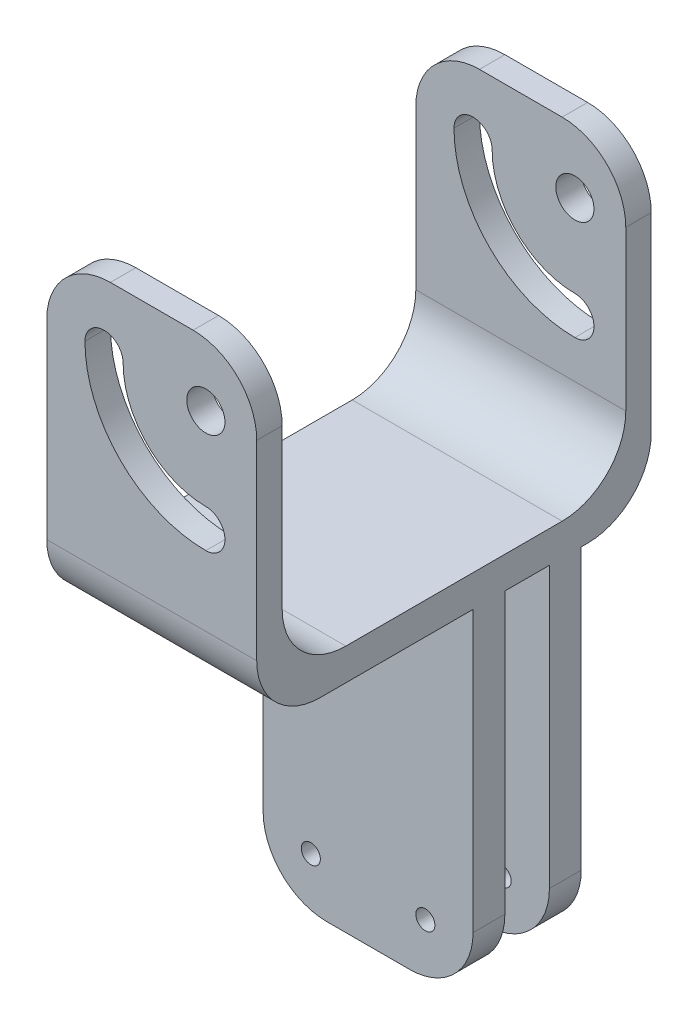
SolidWorks part; units mm, degrees
other "Marcação1"
sketch "Esboço5" plane through (0, 50, 68.25) normal (-0.797, 0.1637, 0.5813) x (0.5636, -0.1442, 0.8134)
material "Nylon - impressão"
ref_plane "Plano frontal" through (0, 0, 0) normal (0, 0, 1) x (1, 0, 0)
ref_plane "Plano superior" through (0, 0, 0) normal (0, 1, 0) x (1, 0, 0)
ref_plane "Plano direito" through (0, 0, 0) normal (1, 0, 0) x (0, 0, -1)
sketch "Esboço1" plane through (0, 0, 0) normal (0, 0, 1) x (1, 0, 0)
  line L0 (0, 0) -> (0, 50)
  line L1 (0, 50) -> (33, 50)
  line L2 (33, 50) -> (33, 0)
  line L3 (33, 0) -> (0, 0)
  line L4 (25, 40) -> (25, 37) construction
  circle A0 centre (25, 40) radius 3
  arc A2 (25, 24) -> (9, 40) centre (25, 40) cw construction
  arc A3 (6, 40) -> (25, 21) centre (25, 40) ccw
  arc A4 (12, 40) -> (25, 27) centre (25, 40) ccw
  arc A5 (12, 40) -> (6, 40) centre (9, 40) ccw
  arc A6 (25, 21) -> (25, 27) centre (25, 24) ccw
  point P10 (13.6863, 28.6863)
  dimension "D3" = 6
  dimension "D5" = 16
  dimension "D6" = 13
  dimension "D1" = 25
  dimension "D2" = 50
  dimension "D4" = 8
extrude "Ressalto-extrusão2" add sketch "Esboço1" along normal blind 62
sketch "Esboço3" plane through (0, 50, 0) normal (0, 1, 0) x (1, 0, 0)
  line L0 (0, -58) -> (33, -58)
  line L1 (0, -62) -> (0, 0) construction
  line L2 (33, -62) -> (33, 0) construction
  line L3 (33, -58) -> (33, -4)
  line L4 (33, -4) -> (0, -4)
  line L5 (0, -4) -> (0, -58)
  line L6 (33, 0) -> (0, 0) construction
  dimension "D1" = 4
  dimension "D2" = 4
extrude "Corte-extrusão1" cut sketch "Esboço3" against normal blind 45
sketch "Esboço7" plane through (0, 0, 0) normal (0, -1, 0) x (1, 0, 0)
  line L0 (0, 11) -> (33, 11)
  line L1 (33, 62) -> (33, 0) construction
  line L2 (0, 62) -> (0, 0) construction
  line L3 (33, 11) -> (33, 16)
  line L4 (33, 16) -> (0, 16)
  line L5 (0, 16) -> (0, 11)
  line L6 (0, 23) -> (33, 23)
  line L7 (33, 23) -> (33, 28)
  line L8 (33, 28) -> (0, 28)
  line L9 (0, 28) -> (0, 23)
  line L10 (33, 4) -> (0, 4) construction
  line L11 (33, 4) -> (0, 4)
  point P2 (0, 0)
  point P5 (0, 0)
  point P10 (0, 0)
  point P15 (0, 0)
  point P18 (0, 0)
  line M10 (33, 0) -> (33, 62)
  line M12 (0, 62) -> (0, 0)
  dimension "D1" = 5
  dimension "D2" = 5
  dimension "D3" = 7
  dimension "D4" = 7
extrude "Ressalto-extrusão3" add sketch "Esboço7" along normal blind 54 contours L8 L6 M10 M12 | L4 L0 M10 M12
sketch "Esboço10" plane through (0, 0, 11) normal (0, 0, -1) x (-1, 0, 0)
  line L0 (0, -54) -> (-33, -54) construction
  line L3 (-7.5, -46) -> (-25.5, -46) construction
  line L4 (0, 0) -> (-33, 0) construction
  circle A5 centre (-25.5, -46) radius 1.5
  circle A6 centre (-7.5, -46) radius 1.5
  point P0 (-16.5, -46)
  point P2 (-16.5, 0)
  dimension "D7" = 3
  dimension "D8" = 3
  dimension "D2" = 8
  dimension "D10" = 18
extrude "Corte-extrusão2" cut sketch "Esboço10" against normal through all
fillet "Filete1" radius 10 12 edges at (16.5, 5, 4) (0, 50, 2) (33, 50, 2) (16.5, 5, 58) (16.5, 0, 62) (16.5, 0, 0) (0, 50, 60) (33, 50, 60) (33, -54, 13.5) (0, -54, 13.5) (33, -54, 25.5) (0, -54, 25.5)
